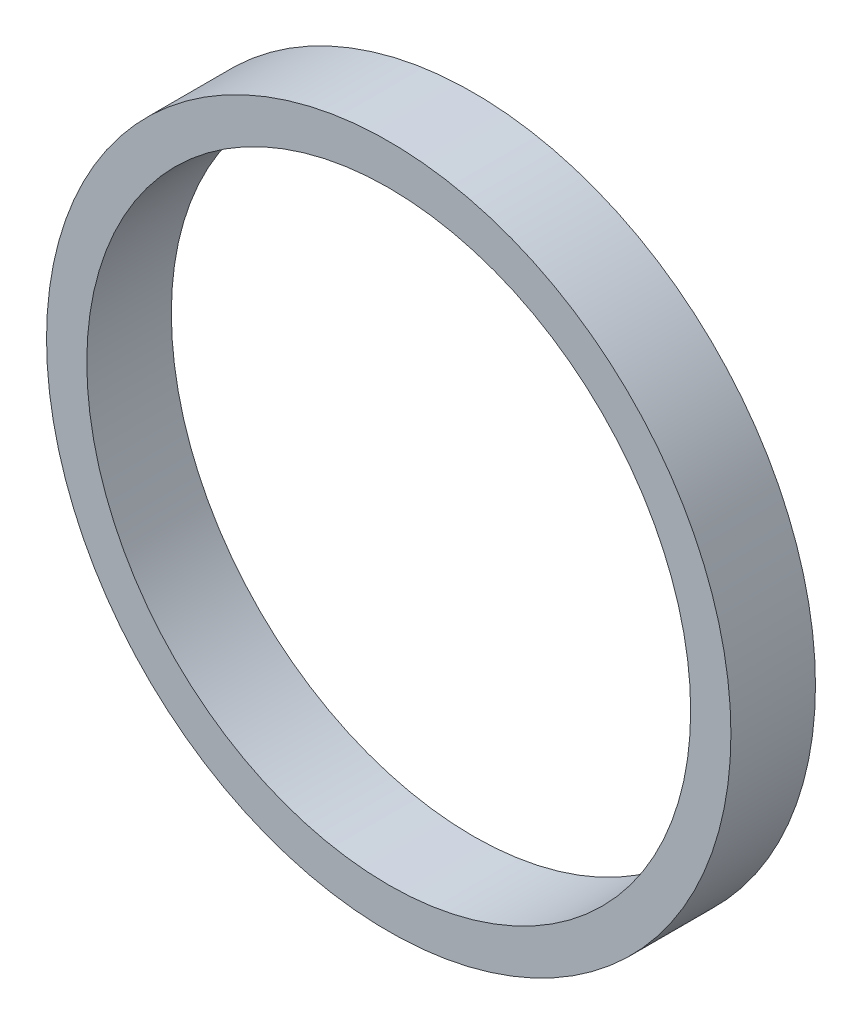
SolidWorks part; units mm, degrees
ref_plane "Front Plane" through (0, 0, 0) normal (0, 0, 1) x (1, 0, 0)
ref_plane "Top Plane" through (0, 0, 0) normal (0, 1, 0) x (1, 0, 0)
ref_plane "Right Plane" through (0, 0, 0) normal (1, 0, 0) x (0, 0, -1)
sketch "Sketch1" plane through (0, 0, 0) normal (0, 0, 1) x (1, 0, 0)
  circle A0 centre (0, 0) radius 7.5
  circle A1 centre (0, 0) radius 8.5
  dimension "D1" = 15
  dimension "D2" = 17
extrude "Boss-Extrude1" add sketch "Sketch1" along normal blind 2.1
